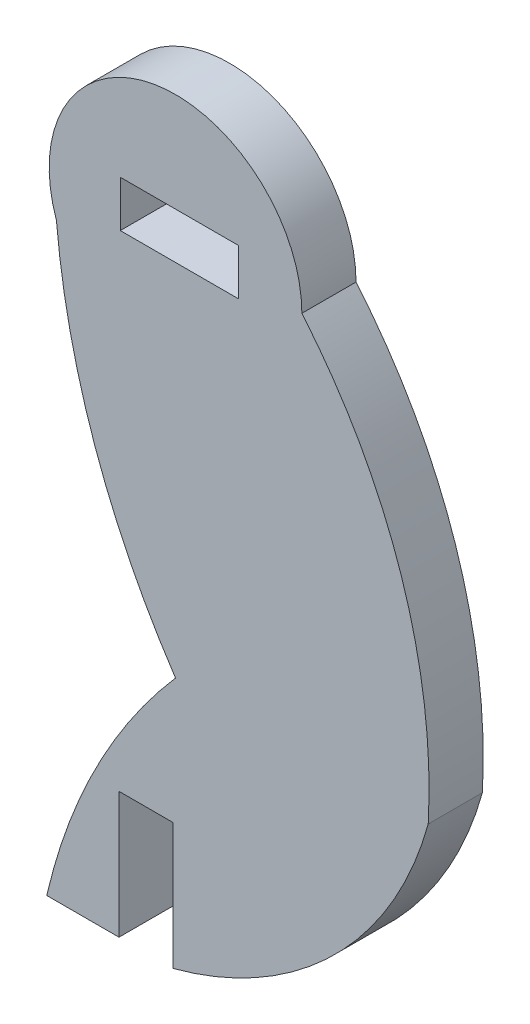
SolidWorks part; units mm, degrees
ref_plane "Alzado" through (0, 0, 0) normal (0, 0, 1) x (1, 0, 0)
ref_plane "Planta" through (0, 0, 0) normal (0, 1, 0) x (1, 0, 0)
ref_plane "Vista lateral" through (0, 0, 0) normal (1, 0, 0) x (0, 0, -1)
sketch "Croquis1" plane through (0, 0, 0) normal (0, 0, 1) x (1, 0, 0)
  line L0 (-3.1317, -35) -> (-7.1317, -35)
  line L1 (0, -21) -> (14, -21) construction
  line L3 (-3.06, 1.5) -> (3.5, 1.5)
  line L4 (-3.06, 1.5) -> (-3.06, -1.06)
  line L5 (-3.06, -1.06) -> (3.5, -1.06)
  line L6 (3.5, 1.5) -> (3.5, -1.06)
  line L10 (-0.1317, -35) -> (-0.1317, -28)
  line L11 (-0.1317, -28) -> (-3.1317, -28)
  line L12 (-3.1317, -35) -> (-3.1317, -28)
  arc A0 (7, 0) -> (-6.5997, -2.3333) centre (0, 0) ccw
  arc A1 (14, -21) -> (11.7823, -26.1118) centre (7, -21) ccw
  arc A2 (-7.1317, -35) -> (0, -21) centre (24.3358, -42.2134) cw
  arc A3 (0, -21) -> (-6.5997, -2.3333) centre (33.2393, 1.2519) cw
  arc A4 (-0.1317, -35) -> (14, -21) centre (-5.2776, -15.6733) ccw
  arc A5 (14, -21) -> (7, 0) centre (-15.9528, -19.3176) ccw
  dimension "D1" = 14
  dimension "D2" = 14
  dimension "D7" = 40
  dimension "D8" = 30
  dimension "D9" = 20
  dimension "D10" = 32.2838
  dimension "D12" = 15.6733
  dimension "D3" = 7
  dimension "D4" = 21
  dimension "D5" = 7
  dimension "D6" = 14
  dimension "D11" = 32.6667
  dimension "D13" = 6.56
  dimension "D14" = 2.56
  dimension "D15" = 7
  dimension "D16" = 3
extrude "Saliente-Extruir1" add sketch "Croquis1" along normal blind 3 contours A1 A5 A0 A3 L3 L6 L5 L4 | A1 L1 | L1 A1 A4 | L10 A4 A1 A2 L0 L12 L11
